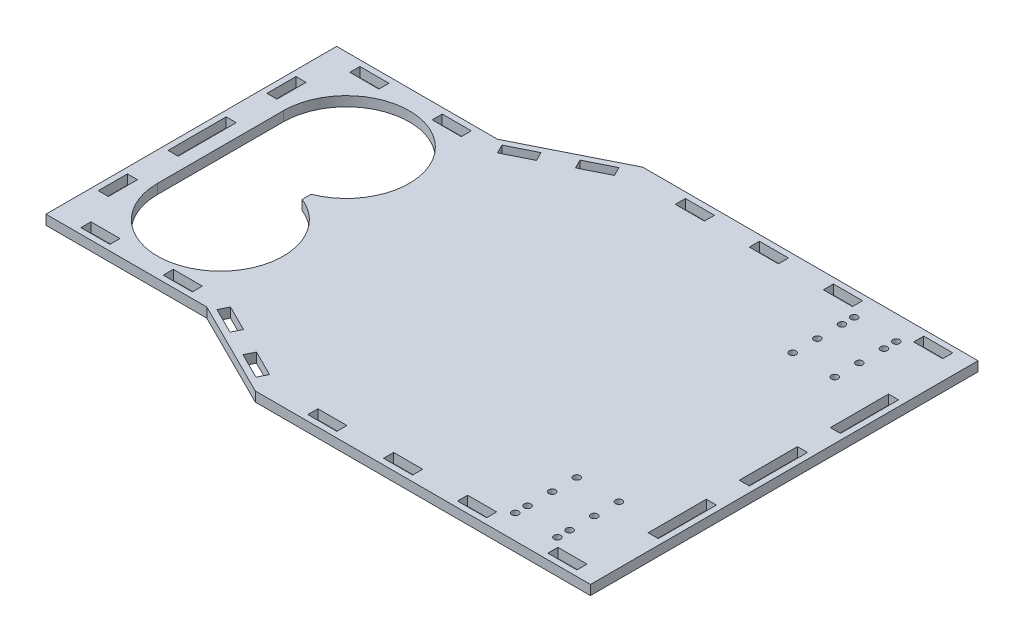
SolidWorks part; units mm, degrees
ref_plane "Front Plane" through (0, 0, 0) normal (0, 0, 1) x (1, 0, 0)
ref_plane "Top Plane" through (0, 0, 0) normal (0, 1, 0) x (1, 0, 0)
ref_plane "Right Plane" through (0, 0, 0) normal (1, 0, 0) x (0, 0, -1)
sketch "Sketch1" plane through (0, 0, 0) normal (0, 1, 0) x (1, 0, 0)
  line L0 (92.5145, -147.0199) -> (92.5145, 52.9801)
  line L1 (92.5145, 52.9801) -> (-80.4855, 52.9801)
  line L2 (-213.4855, -122.0199) -> (-130.4855, -122.0199)
  line L3 (-130.4855, -122.0199) -> (-80.4855, -147.0199)
  line L4 (-130.4855, 27.9801) -> (-213.4855, 27.9801)
  line L5 (-213.4855, 27.9801) -> (-213.4855, -122.0199)
  line L7 (-80.4855, -147.0199) -> (92.5145, -147.0199)
  line L8 (-80.4855, 52.9801) -> (-130.4855, 27.9801)
  line L9 (67.5145, 49.9801) -> (82.5145, 49.9801)
  line L10 (67.5145, 49.9801) -> (67.5145, 44.7801)
  line L11 (67.5145, 44.7801) -> (82.5145, 44.7801)
  line L12 (82.5145, 49.9801) -> (82.5145, 44.7801)
  line L13 (67.5145, 49.9801) -> (82.5145, 44.7801) construction
  line L14 (67.5145, 44.7801) -> (82.5145, 49.9801) construction
  line L15 (67.5145, -138.8199) -> (82.5145, -138.8199)
  line L16 (67.5145, -138.8199) -> (67.5145, -144.0199)
  line L17 (67.5145, -144.0199) -> (82.5145, -144.0199)
  line L18 (82.5145, -138.8199) -> (82.5145, -144.0199)
  line L19 (67.5145, -138.8199) -> (82.5145, -144.0199) construction
  line L20 (67.5145, -144.0199) -> (82.5145, -138.8199) construction
  line L21 (84.3145, 14.9801) -> (89.5145, 14.9801)
  line L22 (84.3145, 14.9801) -> (84.3145, -15.0199)
  line L23 (84.3145, -15.0199) -> (89.5145, -15.0199)
  line L24 (89.5145, 14.9801) -> (89.5145, -15.0199)
  line L25 (84.3145, 14.9801) -> (89.5145, -15.0199) construction
  line L26 (84.3145, -15.0199) -> (89.5145, 14.9801) construction
  line L27 (84.3145, -32.0199) -> (89.5145, -32.0199)
  line L28 (84.3145, -32.0199) -> (84.3145, -62.0199)
  line L29 (84.3145, -62.0199) -> (89.5145, -62.0199)
  line L30 (89.5145, -32.0199) -> (89.5145, -62.0199)
  line L31 (84.3145, -32.0199) -> (89.5145, -62.0199) construction
  line L32 (84.3145, -62.0199) -> (89.5145, -32.0199) construction
  line L33 (84.3145, -79.0199) -> (89.5145, -79.0199)
  line L34 (84.3145, -79.0199) -> (84.3145, -109.0199)
  line L35 (84.3145, -109.0199) -> (89.5145, -109.0199)
  line L36 (89.5145, -79.0199) -> (89.5145, -109.0199)
  line L37 (84.3145, -79.0199) -> (89.5145, -109.0199) construction
  line L38 (84.3145, -109.0199) -> (89.5145, -79.0199) construction
  line L39 (-17.2855, 49.9738) -> (-2.2855, 49.9738)
  line L40 (-17.2855, 49.9738) -> (-17.2855, 44.7738)
  line L41 (-17.2855, 44.7738) -> (-2.2855, 44.7738)
  line L42 (-2.2855, 49.9738) -> (-2.2855, 44.7738)
  line L43 (-17.2855, 49.9738) -> (-2.2855, 44.7738) construction
  line L44 (-17.2855, 44.7738) -> (-2.2855, 49.9738) construction
  line L45 (-55.4855, 49.9738) -> (-40.4855, 49.9738)
  line L46 (-55.4855, 49.9738) -> (-55.4855, 44.7738)
  line L47 (-55.4855, 44.7738) -> (-40.4855, 44.7738)
  line L48 (-40.4855, 49.9738) -> (-40.4855, 44.7738)
  line L49 (-55.4855, 49.9738) -> (-40.4855, 44.7738) construction
  line L50 (-55.4855, 44.7738) -> (-40.4855, 49.9738) construction
  line L51 (80.7283, -47.0199) -> (69.6742, -47.0199) construction
  line L56 (-155.9855, 24.9801) -> (-140.9855, 24.9801)
  line L61 (-155.9855, 24.9801) -> (-155.9855, 19.7801)
  line L62 (-155.9855, 19.7801) -> (-140.9855, 19.7801)
  line L63 (-140.9855, 24.9801) -> (-140.9855, 19.7801)
  line L64 (-155.9855, 24.9801) -> (-140.9855, 19.7801) construction
  line L65 (-155.9855, 19.7801) -> (-140.9855, 24.9801) construction
  line L66 (-198.4855, 24.9801) -> (-183.4855, 24.9801)
  line L67 (-198.4855, 24.9801) -> (-198.4855, 19.7801)
  line L68 (-198.4855, 19.7801) -> (-183.4855, 19.7801)
  line L69 (-183.4855, 24.9801) -> (-183.4855, 19.7801)
  line L70 (-198.4855, 24.9801) -> (-183.4855, 19.7801) construction
  line L71 (-198.4855, 19.7801) -> (-183.4855, 24.9801) construction
  line L72 (-210.4855, 3.9801) -> (-205.2855, 3.9801)
  line L73 (-210.4855, 3.9801) -> (-210.4855, -11.0199)
  line L74 (-210.4855, -11.0199) -> (-205.2855, -11.0199)
  line L75 (-205.2855, 3.9801) -> (-205.2855, -11.0199)
  line L76 (-210.4855, 3.9801) -> (-205.2855, -11.0199) construction
  line L77 (-210.4855, -11.0199) -> (-205.2855, 3.9801) construction
  line L78 (-205.2855, -32.0199) -> (-210.4855, -32.0199)
  line L79 (-205.2855, -32.0199) -> (-205.2855, -62.0199)
  line L80 (-205.2855, -62.0199) -> (-210.4855, -62.0199)
  line L81 (-210.4855, -32.0199) -> (-210.4855, -62.0199)
  line L82 (-205.2855, -32.0199) -> (-210.4855, -62.0199) construction
  line L83 (-205.2855, -62.0199) -> (-210.4855, -32.0199) construction
  line L84 (-205.2855, -83.0199) -> (-210.4855, -83.0199)
  line L85 (-205.2855, -83.0199) -> (-205.2855, -98.0199)
  line L86 (-205.2855, -98.0199) -> (-210.4855, -98.0199)
  line L87 (-210.4855, -83.0199) -> (-210.4855, -98.0199)
  line L88 (-205.2855, -83.0199) -> (-210.4855, -98.0199) construction
  line L89 (-205.2855, -98.0199) -> (-210.4855, -83.0199) construction
  line L94 (-56.3606, -138.8201) -> (-41.3606, -138.8201)
  line L95 (-41.3606, -144.0201) -> (-41.3606, -138.8201)
  line L96 (-56.3606, -144.0201) -> (-41.3606, -144.0201)
  line L97 (-56.3606, -144.0201) -> (-56.3606, -138.8201)
  line L106 (-155.9855, -113.8199) -> (-140.9855, -113.8199)
  line L107 (-140.9855, -119.0199) -> (-140.9855, -113.8199)
  line L108 (-155.9855, -119.0199) -> (-140.9855, -119.0199)
  line L109 (-155.9855, -119.0199) -> (-155.9855, -113.8199)
  line L110 (-198.4855, -113.8199) -> (-183.4855, -113.8199)
  line L111 (-183.4855, -119.0199) -> (-183.4855, -113.8199)
  line L112 (-198.4855, -119.0199) -> (-183.4855, -119.0199)
  line L113 (-198.4855, -119.0199) -> (-198.4855, -113.8199)
  line L114 (20.9145, 49.9801) -> (35.9145, 49.9801)
  line L117 (-153.9855, -47.0199) -> (-153.9855, -44.7234)
  line L118 (-153.9855, -47.0199) -> (-153.9855, -49.3164)
  line L119 (20.9145, 49.9801) -> (20.9145, 44.7801)
  line L120 (20.9145, 44.7801) -> (35.9145, 44.7801)
  line L121 (35.9145, 49.9801) -> (35.9145, 44.7801)
  line L122 (20.9145, 49.9801) -> (35.9145, 44.7801) construction
  line L123 (20.9145, 44.7801) -> (35.9145, 49.9801) construction
  line L124 (20.9145, -138.8199) -> (35.9145, -138.8199)
  line L125 (35.9145, -144.0199) -> (35.9145, -138.8199)
  line L126 (20.9145, -144.0199) -> (35.9145, -144.0199)
  line L127 (20.9145, -144.0199) -> (20.9145, -138.8199)
  line L128 (-17.2855, -138.8136) -> (-2.2855, -138.8136)
  line L129 (-2.2855, -144.0136) -> (-2.2855, -138.8136)
  line L130 (-17.2855, -144.0136) -> (-2.2855, -144.0136)
  line L131 (-17.2855, -144.0136) -> (-17.2855, -138.8136)
  line L132 (-110.9631, 28.5734) -> (-113.2883, 33.2237)
  line L133 (-113.2883, 33.2237) -> (-126.7047, 26.5155)
  line L134 (-86.4555, 46.6401) -> (-84.1303, 41.9898)
  line L135 (-84.1303, 41.9898) -> (-97.5467, 35.2816)
  line L136 (-97.5467, 35.2816) -> (-99.8719, 39.9319)
  line L137 (-99.8719, 39.9319) -> (-86.4555, 46.6401)
  line L138 (-126.7047, 26.5155) -> (-124.3795, 21.8652)
  line L139 (-124.3795, 21.8652) -> (-110.9631, 28.5734)
  line L140 (-99.8719, -133.9717) -> (-86.4555, -140.6799)
  line L141 (-97.5467, -129.3214) -> (-99.8719, -133.9717)
  line L142 (-84.1303, -136.0296) -> (-97.5467, -129.3214)
  line L143 (-86.4555, -140.6799) -> (-84.1303, -136.0296)
  line L144 (-124.3795, -115.905) -> (-110.9631, -122.6132)
  line L145 (-126.7047, -120.5553) -> (-124.3795, -115.905)
  line L146 (-113.2883, -127.2635) -> (-126.7047, -120.5553)
  line L147 (-110.9631, -122.6132) -> (-113.2883, -127.2635)
  line L148 (-198.4855, -79.5199) -> (-198.4855, -14.5199)
  arc A0 (-153.9855, -44.7234) -> (-198.4855, -14.5199) centre (-165.9855, -14.5199) ccw
  arc A1 (-198.4855, -79.5199) -> (-153.9855, -49.3164) centre (-165.9855, -79.5199) ccw
  circle A2 centre (62.8645, -134.4899) radius 1.75
  circle A3 centre (41.1645, -134.4899) radius 1.75
  circle A4 centre (62.8645, -128.1399) radius 1.75
  circle A5 centre (41.1645, -128.1399) radius 1.75
  circle A6 centre (62.8645, -115.4399) radius 1.75
  circle A7 centre (41.1645, -115.4399) radius 1.75
  circle A8 centre (62.8645, -102.7399) radius 1.75
  circle A9 centre (41.1645, -102.7399) radius 1.75
  circle A10 centre (41.1645, 8.7001) radius 1.75
  circle A11 centre (41.1645, 21.4001) radius 1.75
  circle A12 centre (41.1645, 34.1001) radius 1.75
  circle A13 centre (41.1645, 40.4501) radius 1.75
  circle A14 centre (62.8645, 8.7001) radius 1.75
  circle A15 centre (62.8645, 21.4001) radius 1.75
  circle A16 centre (62.8645, 34.1001) radius 1.75
  circle A17 centre (62.8645, 40.4501) radius 1.75
  point P2 (75.0145, 47.3801)
  point P13 (75.0145, -141.4199)
  point P18 (86.9145, -0.0199)
  point P23 (86.9145, -47.0199)
  point P28 (86.9145, -94.0199)
  point P33 (86.9145, -109.0199)
  point P34 (86.9145, 14.9801)
  point P35 (-9.7855, 47.3738)
  point P40 (-47.9855, 47.3738)
  point P45 (-190.9855, 22.3801)
  point P47 (-148.4855, 22.3801)
  point P58 (-213.4855, -47.0199)
  point P59 (92.5145, -47.0199)
  point P65 (-207.8855, -3.5199)
  point P70 (-207.8855, -47.0199)
  point P75 (-207.8855, -90.5199)
  point P110 (28.4145, 47.3801)
  point P117 (20.9145, 47.3801)
  dimension "D59" = 65
  dimension "D60" = 65
  dimension "D62" = 47.5
  dimension "D79" = 3.5
  dimension "D80" = 12.53
  dimension "D82" = 3.5
  dimension "D84" = 6.35
  dimension "D85" = 12.7
  dimension "D86" = 12.7
  dimension "D1" = 200
  dimension "D2" = 173
  dimension "D3" = 5.2
  dimension "D4" = 5.2
  dimension "D5" = 83
  dimension "D6" = 150
  dimension "D7" = 15
  dimension "D8" = 15
  dimension "D9" = 17.5
  dimension "D10" = 17.5
  dimension "D11" = 5.6
  dimension "D12" = 5.6
  dimension "D13" = 5.2
  dimension "D14" = 5.2
  dimension "D15" = 5.2
  dimension "D16" = 5.6
  dimension "D17" = 5.6
  dimension "D18" = 5.6
  dimension "D19" = 30
  dimension "D20" = 30
  dimension "D21" = 30
  dimension "D22" = 38
  dimension "D23" = 38
  dimension "D24" = 47
  dimension "D25" = 5.2
  dimension "D26" = 5.2
  dimension "D27" = 15
  dimension "D28" = 15
  dimension "D29" = 25
  dimension "D30" = 38.2
  dimension "D31" = 63.435
  dimension "D32" = 3.0008
  dimension "D33" = 5.1992
  dimension "D34" = 15
  dimension "D35" = 6.34
  dimension "D36" = 15
  dimension "D37" = 15
  dimension "D38" = 5.2
  dimension "D39" = 306
  dimension "D40" = 50
  dimension "D41" = 3
  dimension "D42" = 15
  dimension "D43" = 5.2
  dimension "D44" = 3
  dimension "D45" = 27.5
  dimension "D46" = 15
  dimension "D47" = 15
  dimension "D48" = 5.2
  dimension "D49" = 3
  dimension "D50" = 30
  dimension "D51" = 5.2
  dimension "D52" = 3
  dimension "D53" = 24
  dimension "D54" = 21
  dimension "D55" = 15
  dimension "D56" = 5.2
  dimension "D57" = 3
  dimension "D58" = 21
  dimension "D61" = 42.5
  dimension "D63" = 47.5
  dimension "D64" = 42.5
  dimension "D65" = 5.2
  dimension "D66" = 15
  dimension "D67" = 3
  dimension "D68" = 23.2
  dimension "D69" = 15
  dimension "D70" = 5.2
  dimension "D71" = 3
  dimension "D72" = 15
  dimension "D73" = 27.5
  dimension "D74" = 15
  dimension "D75" = 5.2
  dimension "D76" = 3
  dimension "D77" = 15
  dimension "D78" = 5.1992
  dimension "D81" = 29.65
  dimension "D83" = 21.7
extrude "Boss-Extrude1" add sketch "Sketch1" along normal blind 5
